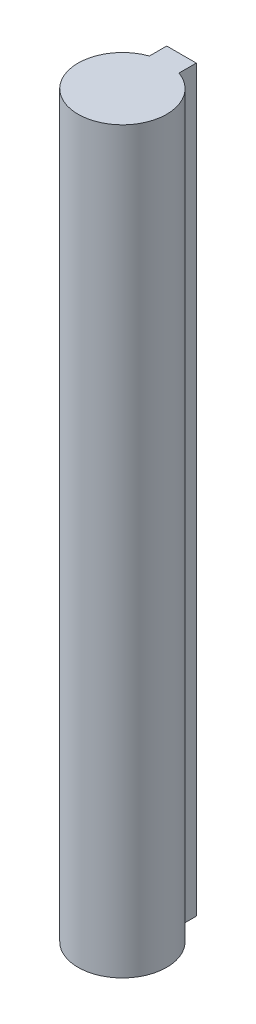
SolidWorks part; units mm, degrees
ref_plane "정면" through (0, 0, 0) normal (0, 0, 1) x (1, 0, 0)
ref_plane "윗면" through (0, 0, 0) normal (0, 1, 0) x (1, 0, 0)
ref_plane "우측면" through (0, 0, 0) normal (1, 0, 0) x (0, 0, -1)
sketch "스케치1" plane through (0, 0, 0) normal (0, 1, 0) x (1, 0, 0)
  circle A0 centre (0, 0) radius 3
  dimension "D1" = 6
extrude "보스-돌출1" add sketch "스케치1" along normal blind 50
sketch "스케치2" plane through (0, 0, 0) normal (0, 1, 0) x (1, 0, 0)
  line L1 (-1, 4) -> (1, 4)
  line L2 (-1, 4) -> (-1, 2)
  line L3 (-1, 2) -> (1, 2)
  line L4 (1, 4) -> (1, 2)
  line L5 (-1, 4) -> (1, 2) construction
  line L6 (-1, 2) -> (1, 4) construction
  circle A0 centre (0, 0) radius 3 construction
  point P0 (0, 3)
  point P7 (0, 2)
  dimension "D1" = 2
  dimension "D2" = 2
extrude "보스-돌출2" add sketch "스케치2" along normal up to surface (50 mm away) up to face at (0, 50, 3)
